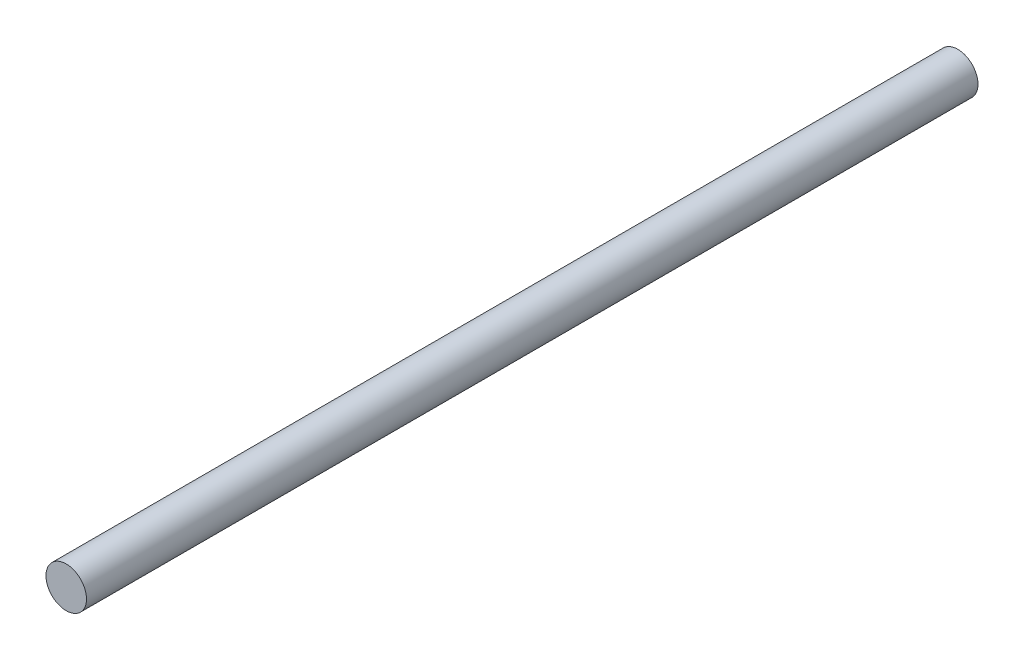
SolidWorks part; units mm, degrees
ref_plane "Alzado" through (0, 0, 0) normal (0, 0, 1) x (1, 0, 0)
ref_plane "Planta" through (0, 0, 0) normal (0, 1, 0) x (1, 0, 0)
ref_plane "Vista lateral" through (0, 0, 0) normal (1, 0, 0) x (0, 0, -1)
sketch "Croquis1" plane through (0, 0, 0) normal (0, 0, 1) x (1, 0, 0)
  circle A0 centre (0, 0) radius 12.5
  dimension "D1" = 25
extrude "Saliente-Extruir1" add sketch "Croquis1" along normal blind 550
